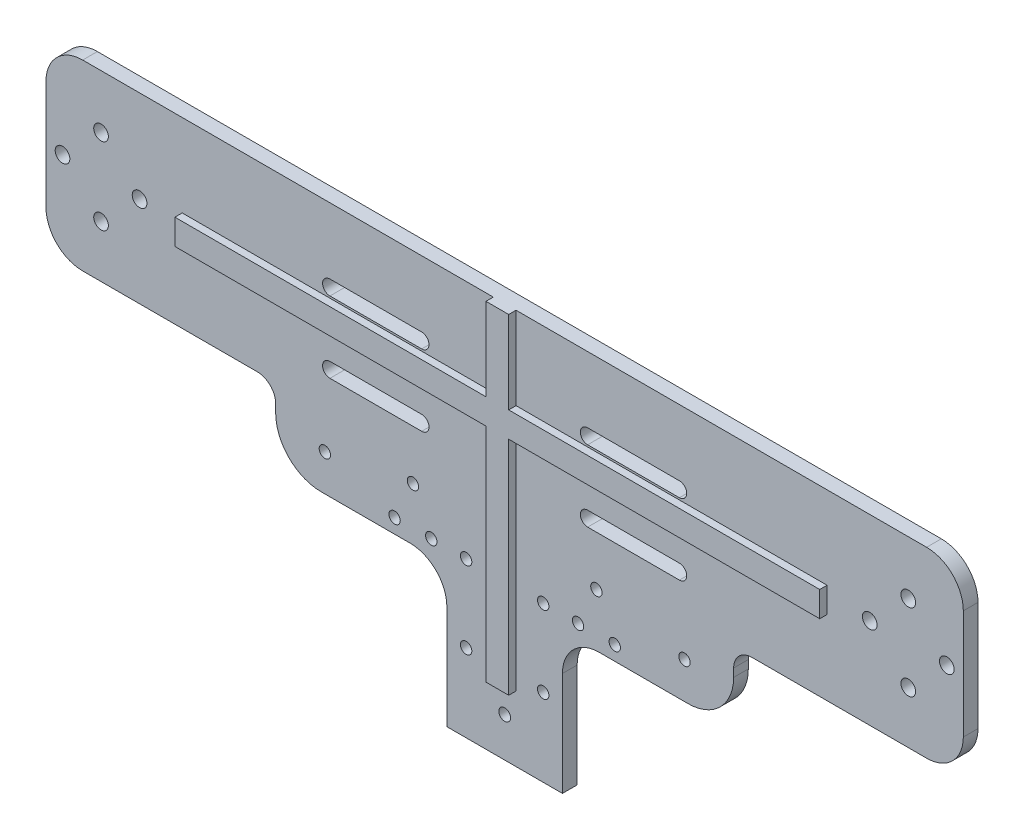
SolidWorks part; units mm, degrees
ref_plane "前视基准面" through (0, 0, 0) normal (0, 0, 1) x (1, 0, 0)
ref_plane "上视基准面" through (0, 0, 0) normal (0, 1, 0) x (1, 0, 0)
ref_plane "右视基准面" through (0, 0, 0) normal (1, 0, 0) x (0, 0, -1)
other "Configuration Table"
sketch "草图1" plane through (0, 0, 0) normal (0, 0, 1) x (1, 0, 0)
  line L0 (-67.4038, 4.4316) -> (-93.2578, 4.4316)
  line L6 (-5.4247, -11.2523) -> (-29.7322, -11.2523) construction
  line L7 (-24.7322, -0.7523) -> (0.2678, -0.7523) construction
  line L8 (-47.6193, 34.2239) -> (-22.6193, 34.2239) construction
  line L9 (-50, -15.1934) -> (-25.75, -15.1934)
  line L10 (-15.75, -25.1934) -> (-15.75, -53.5047)
  line L11 (-15.75, -53.5047) -> (15.75, -53.5047)
  line L12 (0, -53.5047) -> (0, 57.0384) construction
  line L13 (-62.4038, -2.7896) -> (-62.4038, -0.5684)
  line L14 (-95.5508, 54.2203) -> (95.5508, 54.2203)
  line L18 (-47.6193, 36.2239) -> (-22.6193, 36.2239)
  line L21 (-47.6193, 14.7886) -> (-22.6193, 14.7886) construction
  line L22 (-47.6193, 16.7886) -> (-22.6193, 16.7886)
  line L23 (-47.6193, 12.7886) -> (-22.6193, 12.7886)
  line L30 (115, 54.2203) -> (-115, 54.2203)
  line L32 (-115, 4.4316) -> (-93.2578, 4.4316)
  line L33 (47.6193, 14.7886) -> (22.6193, 14.7886) construction
  line L34 (47.6193, 16.7886) -> (22.6193, 16.7886)
  line L35 (47.6193, 12.7886) -> (22.6193, 12.7886)
  line L36 (24.7322, -0.7523) -> (-0.2678, -0.7523) construction
  line L37 (5.4247, -11.2523) -> (29.7322, -11.2523) construction
  line L38 (115, 4.4316) -> (93.2578, 4.4316)
  line L40 (62.4038, -2.7896) -> (62.4038, -0.5684)
  line L41 (15.75, -25.1934) -> (15.75, -53.5047)
  line L42 (50, -15.1934) -> (25.75, -15.1934)
  line L43 (67.4038, 4.4316) -> (93.2578, 4.4316)
  line L44 (-138.9752, 29.1264) -> (-61.5876, 29.1264) construction
  line L45 (-125, 44.2203) -> (-125, 14.4316)
  line L46 (125, 44.2203) -> (125, 14.4316)
  line L47 (-47.6193, 32.2239) -> (-22.6193, 32.2239)
  line L48 (-47.6193, 14.7886) -> (-47.6193, 50.832) construction
  line L49 (47.6193, 34.2239) -> (22.6193, 34.2239) construction
  line L50 (47.6193, 36.2239) -> (22.6193, 36.2239)
  line L51 (47.6193, 32.2239) -> (22.6193, 32.2239)
  arc A1 (0, -21.7489) -> (0.2678, -0.7523) centre (0.2678, -11.2523) cw construction
  circle A17 centre (-110, 29.1264) radius 10.5 construction
  circle A18 centre (-110, 39.6264) radius 2
  circle A19 centre (-99.5, 29.1264) radius 2
  circle A20 centre (-110, 18.6264) radius 2
  circle A21 centre (-120.5, 29.1264) radius 2
  arc A36 (-25.75, -15.1934) -> (-15.75, -25.1934) centre (-25.75, -25.1934) cw
  arc A39 (-50, -15.1934) -> (-62.4038, -2.7896) centre (-50, -2.7896) cw
  arc A43 (-67.4038, 4.4316) -> (-62.4038, -0.5684) centre (-67.4038, -0.5684) cw
  arc A46 (-47.6193, 16.7886) -> (-47.6193, 12.7886) centre (-47.6193, 14.7886) ccw
  arc A47 (-22.6193, 12.7886) -> (-22.6193, 16.7886) centre (-22.6193, 14.7886) ccw
  circle A52 centre (0, -42.7523) radius 1.6
  arc A53 (1.5953, -42.6304) -> (-1.5953, -42.6304) centre (0, -32.2523) cw construction
  arc A56 (47.6193, 16.7886) -> (47.6193, 12.7886) centre (47.6193, 14.7886) cw
  arc A57 (22.6193, 12.7886) -> (22.6193, 16.7886) centre (22.6193, 14.7886) cw
  circle A58 centre (110, 29.1264) radius 10.5 construction
  arc A59 (0, -21.7489) -> (-0.2678, -0.7523) centre (-0.2678, -11.2523) ccw construction
  arc A60 (67.4038, 4.4316) -> (62.4038, -0.5684) centre (67.4038, -0.5684) ccw
  arc A61 (50, -15.1934) -> (62.4038, -2.7896) centre (50, -2.7896) ccw
  arc A62 (25.75, -15.1934) -> (15.75, -25.1934) centre (25.75, -25.1934) ccw
  circle A63 centre (120.5, 29.1264) radius 2
  circle A64 centre (110, 18.6264) radius 2
  circle A65 centre (99.5, 29.1264) radius 2
  circle A66 centre (110, 39.6264) radius 2
  circle A77 centre (49, -5.2523) radius 1.55
  circle A78 centre (-10.5, -32.2523) radius 1.55
  circle A79 centre (0, -21.7489) radius 1.5466
  circle A80 centre (0, -0.7523) radius 1.55
  circle A81 centre (-49, -5.2523) radius 1.55
  circle A82 centre (-25, -0.7523) radius 1.55
  circle A83 centre (-30, -11.2523) radius 1.55
  circle A84 centre (-20, -11.2523) radius 1.55
  circle A85 centre (-10.5, -11.2523) radius 1.55
  circle A86 centre (30, -11.2523) radius 1.55
  circle A87 centre (20, -11.2523) radius 1.55
  circle A88 centre (25, -0.7523) radius 1.55
  circle A89 centre (10.5, -11.2523) radius 1.55
  circle A90 centre (10.5, -32.2523) radius 1.55
  arc A91 (-47.6193, 36.2239) -> (-47.6193, 32.2239) centre (-47.6193, 34.2239) ccw
  arc A92 (-22.6193, 32.2239) -> (-22.6193, 36.2239) centre (-22.6193, 34.2239) ccw
  arc A93 (47.6193, 36.2239) -> (47.6193, 32.2239) centre (47.6193, 34.2239) cw
  arc A94 (22.6193, 32.2239) -> (22.6193, 36.2239) centre (22.6193, 34.2239) cw
  arc A95 (125, 44.2203) -> (115, 54.2203) centre (115, 44.2203) ccw
  arc A96 (125, 14.4316) -> (115, 4.4316) centre (115, 14.4316) cw
  arc A97 (-125, 14.4316) -> (-115, 4.4316) centre (-115, 14.4316) ccw
  arc A98 (-125, 44.2203) -> (-115, 54.2203) centre (-115, 44.2203) cw
  point P2 (0, 54.2203)
  point P6 (-35.1193, 34.2239)
  point P15 (-35.1193, 14.7886)
  point P28 (0, 0)
  point P31 (35.1193, 34.2239)
  point P35 (35.1193, 14.7886)
  point P59 (0, 54.2203)
  point P98 (-62.4038, -0.4926)
  point P99 (0, 9.7477)
  point P102 (-34.7322, -0.2523)
  point P109 (0, 54.2203)
  point P115 (125, 54.2203)
  point P119 (0, 54.2203)
  point P120 (34.7322, -0.2523)
  point P121 (62.4038, -0.4926)
  point P124 (150, 4.4316)
  point P125 (125, 4.4316)
  point P127 (-150, 4.4316)
  point P130 (150, 54.2203)
  point P131 (-125, 4.4316)
  point P133 (-150, 54.2203)
  point P155 (-125, 54.2203)
  dimension "D1" = 21
  dimension "D2" = 4
  dimension "D3" = 10
  dimension "D4" = 4
  dimension "D5" = 220
  dimension "D9" = 3.2
  dimension "D8" = 25
  dimension "D10" = 125
  dimension "D11" = 28.3113
  dimension "D13" = 24.25
extrude "凸台-拉伸1" add sketch "草图1" along normal blind 4
sketch "草图2" plane through (0, 0, 4) normal (0, 0, 1) x (1, 0, 0)
  line L0 (0, 67.4496) -> (0, -73.2238) construction
  line L1 (3.0985, -35.6587) -> (-3.0985, -35.6587)
  line L2 (-3.0985, -35.6587) -> (-3.0985, 24.7818)
  line L3 (-3.0985, 54.2203) -> (3.0985, 54.2203)
  line L4 (115, 54.2203) -> (-115, 54.2203) construction
  line L5 (-3.0985, 31.6938) -> (-3.0985, 54.2203)
  line L6 (-87.8699, 31.6938) -> (-3.0985, 31.6938)
  line L7 (-87.8699, 31.6938) -> (-87.8699, 24.7818)
  line L8 (-87.8699, 24.7818) -> (-3.0985, 24.7818)
  line L10 (3.0985, 31.6938) -> (3.0985, 54.2203)
  line L11 (3.0985, -35.6587) -> (3.0985, 24.7818)
  line L12 (87.8699, 24.7818) -> (3.0985, 24.7818)
  line L13 (87.8699, 31.6938) -> (87.8699, 24.7818)
  line L14 (87.8699, 31.6938) -> (3.0985, 31.6938)
  point P9 (-59.2488, 28.2378)
  point P14 (0, -35.6587)
  point P15 (0, 54.2203)
extrude "凸台-拉伸2" add sketch "草图2" along normal blind 2
